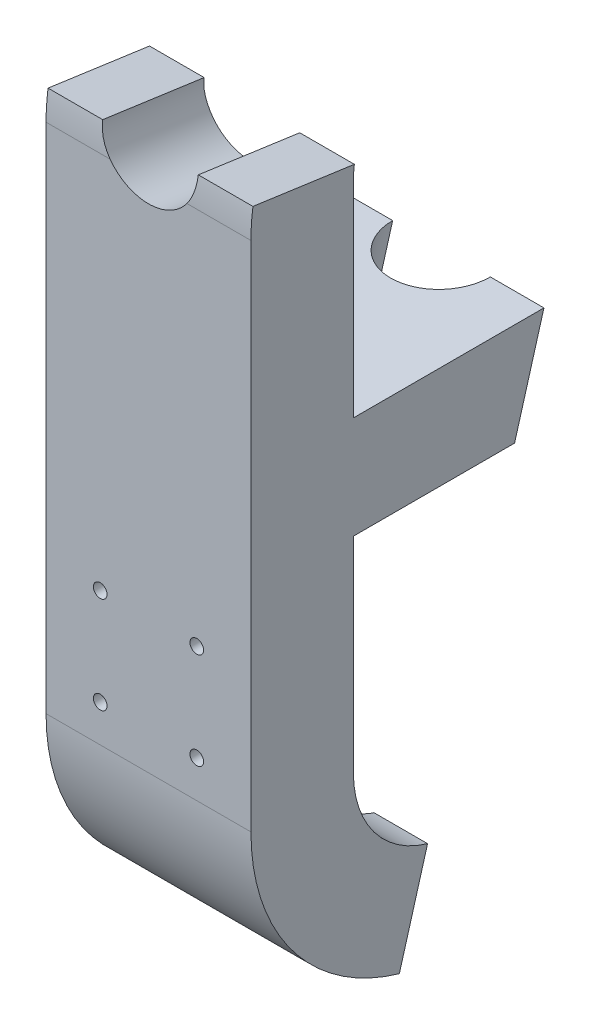
SolidWorks part; units mm, degrees
ref_plane "前视基准面" through (0, 0, 0) normal (0, 0, 1) x (1, 0, 0)
ref_plane "上视基准面" through (0, 0, 0) normal (0, 1, 0) x (1, 0, 0)
ref_plane "右视基准面" through (0, 0, 0) normal (1, 0, 0) x (0, 0, -1)
sketch "草图1" plane through (0, 0, 0) normal (0, 0, 1) x (1, 0, 0)
  line L1 (-30, 75) -> (30, 75)
  line L2 (-30, 75) -> (-30, -75)
  line L3 (-30, -75) -> (30, -75)
  line L4 (30, 75) -> (30, -75)
  line L5 (-30, 75) -> (30, -75) construction
  line L6 (-30, -75) -> (30, 75) construction
  point P0 (0, 0)
  dimension "D1" = 60
  dimension "D2" = 150
extrude "凸台-拉伸1" add sketch "草图1" against normal blind 30
sketch "草图2" plane through (0, 0, -30) normal (0, 0, -1) x (-1, 0, 0)
  line L0 (30, 75) -> (30, -75) construction
  line L1 (-30, -75) -> (-30, 75) construction
  line L2 (30, -75) -> (-30, -75) construction
  line L3 (30, 75) -> (30, -75)
  line L4 (-30, -75) -> (-30, 75)
  line L5 (30, -75) -> (-30, -75)
  line L7 (-14.1421, -64.1421) -> (14.1421, -64.1421) construction
  line L8 (-14.1421, -64.1421) -> (-14.1421, -35.8579) construction
  line L9 (-14.1421, -35.8579) -> (14.1421, -35.8579) construction
  line L10 (14.1421, -64.1421) -> (14.1421, -35.8579) construction
  line L11 (-14.1421, -64.1421) -> (14.1421, -35.8579) construction
  line L12 (-14.1421, -35.8579) -> (14.1421, -64.1421) construction
  circle A0 centre (0, -50) radius 20 construction
  circle A1 centre (-14.1421, -35.8579) radius 5
  circle A2 centre (14.1421, -35.8579) radius 5
  circle A3 centre (14.1421, -64.1421) radius 5
  circle A4 centre (-14.1421, -64.1421) radius 5
  dimension "D3" = 40
  dimension "D4" = 10
  dimension "D5" = 10
  dimension "D6" = 10
  dimension "D7" = 10
  dimension "D1" = 30
  dimension "D2" = 25
extrude "切除-拉伸1" cut sketch "草图2" against normal blind 18 contours A1 | A2 | A4 | A3
sketch "草图6" plane through (0, 0, -12) normal (0, 0, -1) x (-1, 0, 0)
  circle A0 centre (-14.1421, -64.1421) radius 5 construction
  circle A1 centre (14.1421, -64.1421) radius 5 construction
  circle A2 centre (14.1421, -35.8579) radius 5 construction
  circle A3 centre (-14.1421, -35.8579) radius 5 construction
  circle A4 centre (-14.1421, -64.1421) radius 5
  circle A5 centre (14.1421, -64.1421) radius 5
  circle A6 centre (14.1421, -35.8579) radius 5
  circle A7 centre (-14.1421, -35.8579) radius 5
  circle A8 centre (-14.1421, -35.8579) radius 2
  circle A9 centre (14.1421, -35.8579) radius 2
  circle A10 centre (-14.1421, -64.1421) radius 2
  circle A11 centre (14.1421, -64.1421) radius 2
  dimension "D1" = 4
  dimension "D2" = 4
  dimension "D3" = 4
  dimension "D4" = 4
extrude "切除-拉伸2" cut sketch "草图6" against normal through all contours A11 | A10 | A8 | A9
sketch "草图7" plane through (30, 0, 0) normal (1, 0, 0) x (0, 0, -1)
  line L0 (60, -75) -> (43.4618, -132.6757)
  line L4 (0, 75) -> (0, -75)
  line L5 (0, -75) -> (30, -75)
  line L6 (30, -75) -> (30, 75)
  line L7 (30, 75) -> (0, 75)
  line L8 (0, 75) -> (0, -75)
  line L9 (0, -75) -> (30, -75)
  line L10 (30, -75) -> (30, 75)
  line L11 (30, 75) -> (0, 75)
  arc A0 (0, -75) -> (43.4618, -132.6757) centre (60, -75) ccw
  arc A1 (30, -75) -> (51.7309, -103.8379) centre (60, -75) ccw
  line M7 (0, -75) -> (30, -75)
  dimension "D2" = 16
  dimension "D3" = 30
  dimension "D1" = 0
extrude "凸台-拉伸2" add sketch "草图7" against normal up to surface (60 mm away) contours A1 A0 L0 M7 up to face at (-30, 0, -15)
sketch "草图8" plane through (0, 0, -30) normal (0, 0, -1) x (-1, 0, 0)
  line L0 (30, 75) -> (30, -75) construction
  line L1 (-30, -75) -> (-30, 75) construction
  line L2 (30, 75) -> (30, -75)
  line L3 (-30, -75) -> (-30, 75)
  line L5 (-30, 15) -> (30, 15)
  line L6 (-30, 15) -> (-30, -15)
  line L7 (-30, -15) -> (30, -15)
  line L8 (30, 15) -> (30, -15)
  line L9 (-30, 15) -> (30, -15) construction
  line L10 (-30, -15) -> (30, 15) construction
  point P4 (0, 0)
  point P6 (0, 0)
  dimension "D1" = 30
extrude "凸台-拉伸3" add sketch "草图8" along normal blind 60 contours L3 L7 L2 L5
sketch "草图9" plane through (0, -21.5958, -75.3134) normal (0, -0.2756, -0.9613) x (-1, 0, 0)
  line L2 (-69.5479, 54.8451) -> (69.5479, 54.8451)
  line L3 (-69.5479, 54.8451) -> (-69.5479, -54.8451)
  line L4 (-69.5479, -54.8451) -> (69.5479, -54.8451)
  line L5 (69.5479, 54.8451) -> (69.5479, -54.8451)
  line L6 (-69.5479, 54.8451) -> (69.5479, -54.8451) construction
  line L7 (-69.5479, -54.8451) -> (69.5479, 54.8451) construction
  point P0 (0, 0)
extrude "切除-拉伸3" cut sketch "草图9" along normal through all
ref_plane "基准面1" through (30, -132.6757, -43.4618) normal (0, -0.9613, 0.2756) x (-1, 0, 0)
sketch "草图10" plane through (30, -132.6757, -43.4618) normal (0, -0.9613, 0.2756) x (-1, 0, 0)
  line L0 (60, 0) -> (0, 0) construction
  line L1 (60, 0) -> (0, 0)
  circle A0 centre (30, 0) radius 14.3
  dimension "D1" = 28.6
extrude "切除-拉伸4" cut sketch "草图10" against normal through all contours L1 A0 | L1 A0
sketch "草图11" plane through (0, 0, 0) normal (1, 0, 0) x (0, 0, -1)
  line L1 (30, 75) -> (0, 75) construction
  line L2 (60, 75) -> (0.5839, 83.3504)
  line L3 (30, 75) -> (0, 75)
  arc A0 (30, 75) -> (30.292, 79.1752) centre (60, 75) cw
  arc A1 (0, 75) -> (0.5839, 83.3504) centre (60, 75) cw
  dimension "D1" = 8
  dimension "D2" = 30
extrude "凸台-拉伸4" add sketch "草图11" against normal mid plane 60
ref_plane "基准面2" through (30, 83.3504, -0.5839) normal (0, 0.1392, 0.9903) x (1, 0, 0)
sketch "草图12" plane through (30, 83.3504, -0.5839) normal (0, 0.1392, 0.9903) x (1, 0, 0)
  line L0 (-60, 0) -> (0, 0) construction
  line L1 (-60, 0) -> (0, 0)
  circle A0 centre (-30, 0) radius 14
  dimension "D1" = 28
extrude "切除-拉伸5" cut sketch "草图12" against normal through all contours L1 A0 | L1 A0
